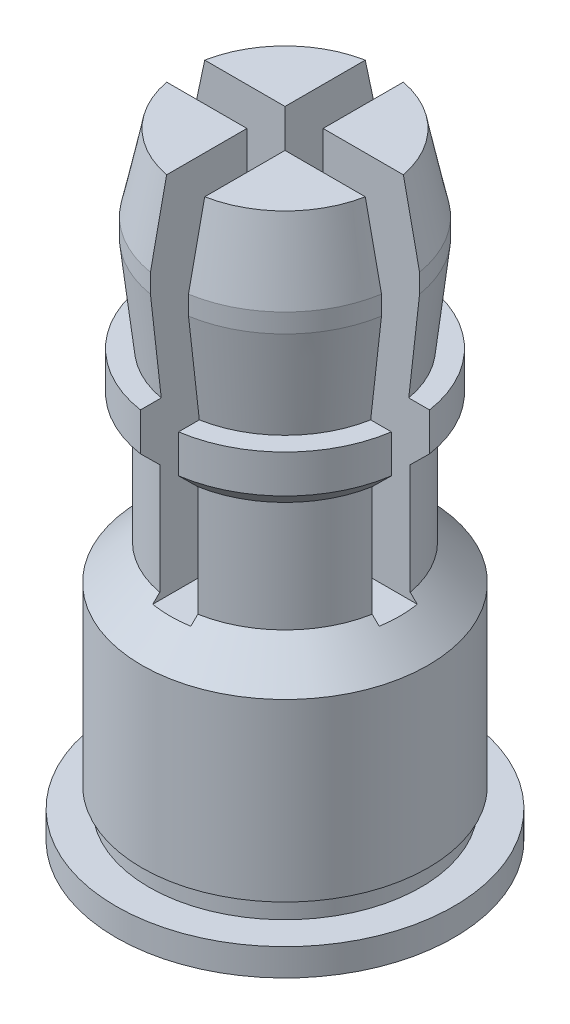
SolidWorks part; units mm, degrees
revolve "Body" add sketch "BodySke" angle 360 about L9
sketch "BodySke" plane through (0, 0, 0) normal (0, 0, 1) x (1, 0, 0)
  line L0 (2.5555, 0.51) -> (2.5555, 0.8925)
  line L1 (2.69, 4.1891) -> (2.0272, 4.8518)
  line L3 (2.0272, 4.8518) -> (2.0272, 6.9267)
  line L4 (0, 0) -> (3.175, 0)
  line L5 (3.175, 0) -> (3.175, 0.51)
  line L6 (3.175, 0.51) -> (2.5555, 0.51)
  line L7 (2.385, 7.2845) -> (2.385, 8)
  line L8 (2.69, 0.8925) -> (2.69, 4.1891)
  line L9 (0, 0) -> (0, 17.145) construction
  line L10 (2.385, 8) -> (2, 8)
  line L11 (2, 8) -> (2.2, 9.79)
  line L12 (2.2, 9.79) -> (2.2, 10.148)
  line L13 (2.2, 10.148) -> (1.9, 11.58)
  line L14 (1.9, 11.58) -> (0, 11.58)
  line L15 (2.5555, 0.8925) -> (2.69, 0.8925)
  line L17 (0, 11.58) -> (0, 0)
  line L19 (2.385, 7.2845) -> (2.0272, 6.9267)
  dimension "H_dia" = 6.35
  dimension "C_dia" = 5.38
  dimension "Groove_dia" = 5.111
  dimension "T_ht" = 0.51
  dimension "Groove_wid" = 0.3825
  dimension "D_ht" = 3.58
  dimension "Neck_dia" = 4.0545
  dimension "B_dia" = 4.77
  dimension "B_ht" = 0.7155
  dimension "Panel_dia" = 4
  dimension "Slip_dia" = 4.4
  dimension "Tip_dia" = 3.8
  dimension "Grip_ht" = 1.79
  dimension "Slip_ht" = 0.358
  dimension "Neck_len" = 3.1482
  dimension "D1" = 315
  dimension "Length" = 8
ref_plane "Plane1" through (0, 0, 0) normal (0, 0, 1) x (1, 0, 0)
ref_plane "Plane2" through (0, 0, 0) normal (0, 1, 0) x (1, 0, 0)
ref_plane "Plane3" through (0, 0, 0) normal (1, 0, 0) x (0, 0, -1)
sketch "SlitCutSke" plane through (0, 11.58, 0) normal (0, 1, 0) x (-1, 0, 0)
  line L0 (-2.6661, 0.3578) -> (2.6661, 0.3578)
  line L1 (2.6661, -0.3578) -> (-2.6661, -0.3578)
  line L2 (-2.6661, 0.3578) -> (-2.6661, -0.3578)
  line L3 (2.6661, 0.3578) -> (2.6661, -0.3578)
  line L4 (-4.064, 0) -> (4.064, 0) construction
  circle A1 centre (0, 0) radius 2.69 construction
extrude "SlitCut" cut sketch "SlitCutSke" against normal blind 6.8582
pattern_circular "SlitCutPat" count 2 every 90 about axis through (0, 0, 0) along (0, 1, 0) of "SlitCut"
ref_plane "Plane4" through (0, -0.5486, 0) normal (0, 1, 0) x (-1, 0, 0)
equation "' \"Panel_dia@BodySke\" = 4"
equation "' \"Length@BodySke\" = 8"
equation "' \"B_dia@BodySke\" = 4.77"
equation "' \"C_dia@BodySke\" = 5.38"
equation "' \"D_ht@BodySke\" = 3.58"
equation "' \"H_dia@BodySke\" = 6.35"
equation "' \"T_ht@BodySke\" = 0.51"
equation "\"Tip_dia@BodySke\" = \"Panel_dia@BodySke\" * 0.95"
equation "\"Slip_dia@BodySke\" = \"Panel_dia@BodySke\" * 1.1"
equation "\"Slip_ht@BodySke\" = \"D_ht@BodySke\" * 0.1"
equation "\"Grip_ht@BodySke\" = \"D_ht@BodySke\" * 0.5"
equation "\"B_ht@BodySke\" = \"B_dia@BodySke\" * 0.15"
equation "\"Neck_dia@BodySke\" = \"B_dia@BodySke\" * 0.85"
equation "\"Neck_len@BodySke\" = \"B_dia@BodySke\" * 0.66"
equation "\"Groove_dia@BodySke\" = \"C_dia@BodySke\" * 0.95"
equation "\"Groove_wid@BodySke\" = \"T_ht@BodySke\" * 0.75"
equation "\"Width@SlitCutSke\" = \"B_ht@BodySke\""
equation "\"Depth@SlitCut\" = \"D_ht@BodySke\" + \"Neck_len@BodySke\" + 0.13"
